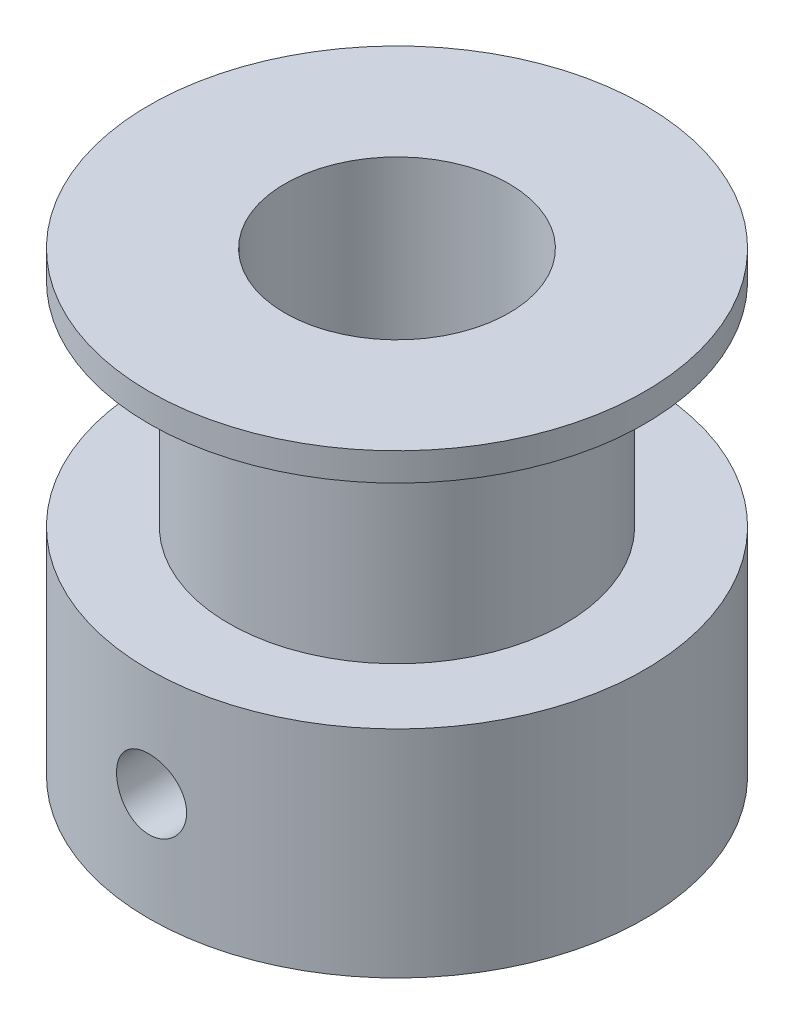
SolidWorks part; units mm, degrees
material "aluminio"
ref_plane "Alzado" through (0, 0, 0) normal (0, 0, 1) x (1, 0, 0)
ref_plane "Planta" through (0, 0, 0) normal (0, 1, 0) x (1, 0, 0)
ref_plane "Vista lateral" through (0, 0, 0) normal (1, 0, 0) x (0, 0, -1)
sketch "Croquis1" plane through (0, 0, 0) normal (0, 1, 0) x (1, 0, 0)
  circle A0 centre (0, 0) radius 8.85
  dimension "D1" = 17.7
extrude "Saliente-Extruir1" add sketch "Croquis1" along normal blind 7.7
sketch "Croquis2" plane through (0, 7.7, 0) normal (0, 1, 0) x (1, 0, 0)
  circle A0 centre (0, 0) radius 6
  dimension "D1" = 12
extrude "Saliente-Extruir2" add sketch "Croquis2" along normal blind 7.6
sketch "Croquis3" plane through (0, 15.3, 0) normal (0, 1, 0) x (1, 0, 0)
  circle A0 centre (0, 0) radius 8.85
  circle A1 centre (0, 0) radius 8.85 construction
extrude "Saliente-Extruir3" add sketch "Croquis3" along normal blind 1
sketch "Croquis4" plane through (0, 16.3, 0) normal (0, 1, 0) x (1, 0, 0)
  circle A0 centre (0, 0) radius 4
  dimension "D1" = 8
extrude "Cortar-Extruir1" cut sketch "Croquis4" against normal through all
hole_wizard "Taladro roscado M31 (definir posicio)" positions "Croquis6" profile "Croquis5" tap size "M3" standard "Iso"
sketch "Croquis6" plane through (0, 0, 0) normal (0, 0, 1) x (1, 0, 0)
  line L0 (0, 7.7) -> (0, 0) construction
  line L1 (8.85, 7.7) -> (-8.85, 7.7) construction
  point P0 (0, 3.85)
sketch "Croquis5" plane through (0, 3.85, 0) normal (1, 0, 0) x (0, 1, 0)
  line L0 (0, 0) -> (0, 8.851)
  line L1 (0, 8.851) -> (1.25, 8.851)
  line L2 (1.25, 8.851) -> (1.25, 0)
  line L5 (1.25, 0) -> (0, 0)
  line L11 (0, -6.35) -> (0, 107.95) construction
  dimension "Diámetro de perforador para roscar hasta el siguiente" = 2.5
  dimension "Profundidad de perforador para roscar hasta el siguiente" = 8.851
cosmetic thread "Rosca de taladro1" parameters "D2"=3
cosmetic thread "Rosca cosmética1" parameters "D2"=3
pattern_circular "MatrizC1" count 2 over 90 about axis through (0, 7.7, 0) along (0, -1, 0) of "Taladro roscado M31 (definir posicio)"
cosmetic thread "Rosca cosmética2" parameters "D2"=3
